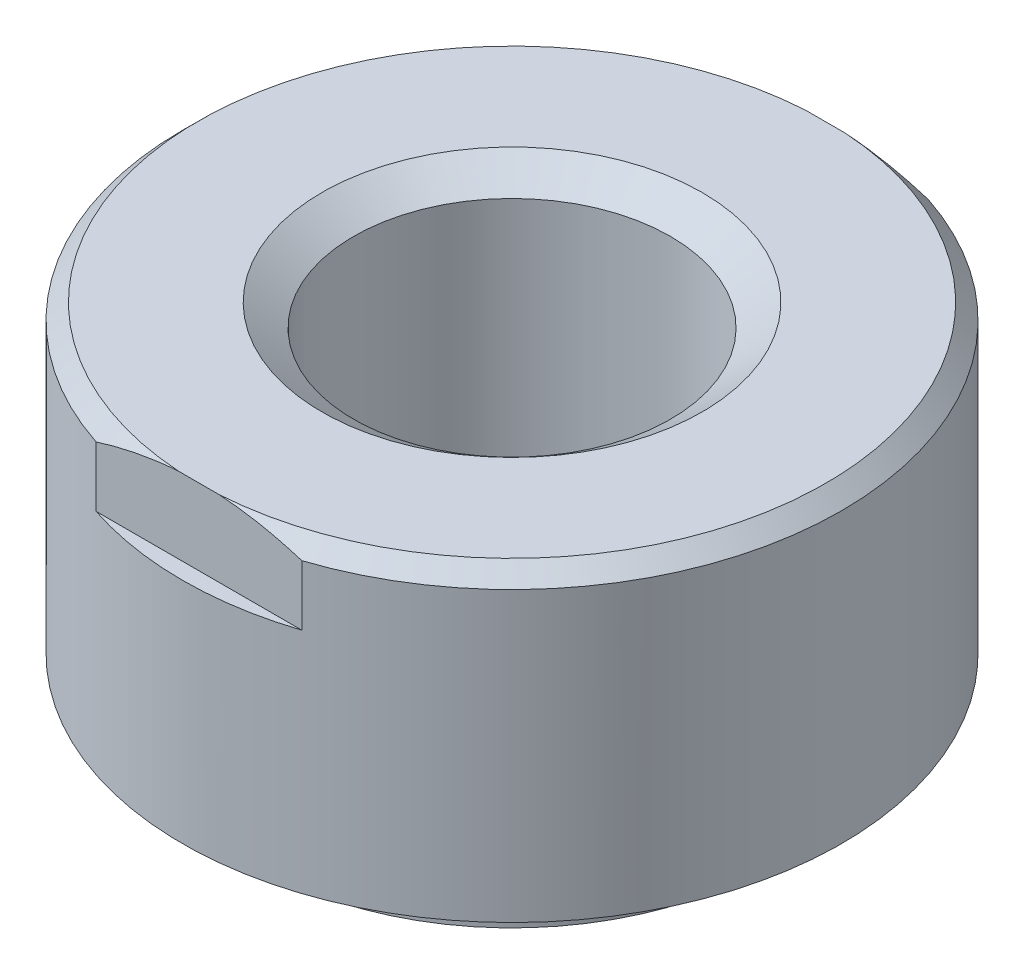
SolidWorks part; units mm, degrees
revolve "Body" add sketch "BodySke"
sketch "BodySke" plane through (0, 0, 0) normal (0, 0, 1) x (1, 0, 0)
  line L0 (5.9003, 0) -> (6.3373, 0)
  line L1 (8.255, 0) -> (8.255, 7.62)
  line L2 (8.255, 7.62) -> (3.9688, 7.62)
  line L3 (3.9688, 7.62) -> (3.9688, -1.4732)
  line L4 (3.9688, -1.4732) -> (6.3373, -1.4732)
  line L5 (6.3373, -1.4732) -> (6.3373, -1.3462)
  line L6 (6.3373, -1.3462) -> (5.9003, -0.5893)
  line L7 (1.016, 1.5875) -> (3.6522, 1.5875) construction
  line L8 (6.3373, -0.5893) -> (7.2961, -0.5893)
  line L9 (0, 0) -> (0, 15.24) construction
  line L10 (5.9003, -0.5893) -> (5.9003, 0)
  line L11 (7.2961, -0.5893) -> (7.2961, 0)
  line L12 (6.3373, -0.5893) -> (6.3373, 0)
  line L13 (7.2961, 0) -> (8.255, 0)
  dimension "D1" = 60
  dimension "E_dia" = 16.51
  dimension "C_dia" = 12.6746
  dimension "A_ht" = 1.4732
  dimension "T_ht" = 7.62
  dimension "Thread_min" = 7.9375
  dimension "C_len" = 0.127
  dimension "Clinching_ht" = 0.5893
  dimension "Advance" = 1.5875
  dimension "Clinching_dia" = 14.5923
cosmetic thread "ThreadCosmetic" [suppressed]
revolve "EndChamfer" cut sketch "EndChamferSke" angle 360 about L0
sketch "EndChamferSke" plane through (0, 0, 0) normal (0, 0, 1) x (1, 0, 0)
  line L0 (0, -2.54) -> (0, 7.62) construction
  line L1 (0, 0) -> (0, 15.24) construction
  line L2 (4.7625, -1.7272) -> (4.7625, -1.4707)
  line L3 (4.7625, -1.4707) -> (3.9688, -0.9151)
  line L4 (3.9688, -0.9151) -> (3.9688, -1.7272)
  line L5 (3.9688, -1.7272) -> (4.7625, -1.7272)
  line L6 (4.7625, 7.62) -> (3.9688, 7.0644)
  line L8 (3.9688, 7.0644) -> (3.9688, 7.62)
  line L9 (4.7625, 7.62) -> (3.9688, 7.62)
  line L10 (3.9688, 7.62) -> (-3.9688, 7.62) construction
  line L11 (-6.3373, -1.4732) -> (6.3373, -1.4732) construction
  dimension "D1" = 0.254
  dimension "Thread_nominal" = 9.525
  dimension "D2" = 34.99
  dimension "Thread_min" = 7.9375
  dimension "Inset" = 0.0025
ref_plane "Plane1" through (0, 0, 0) normal (0, 0, 1) x (1, 0, 0)
ref_plane "Plane2" through (0, 0, 0) normal (0, 1, 0) x (1, 0, 0)
ref_plane "Plane3" through (0, 0, 0) normal (1, 0, 0) x (0, 0, -1)
chamfer "Chamfer" distance 0.3969 1 edges at (0, 7.62, -8.255)
sketch "FlatsSke" plane through (0, 7.62, 0) normal (0, 1, 0) x (-1, 0, 0)
  line L0 (-8.255, 7.8423) -> (8.255, 7.8423)
  line L1 (8.255, 7.8423) -> (8.255, 8.6678)
  line L2 (8.255, 8.6678) -> (-8.255, 8.6678)
  line L3 (-8.255, 8.6678) -> (-8.255, 7.8423)
  line L4 (-8.255, -7.8423) -> (8.255, -7.8422)
  line L5 (8.255, -7.8422) -> (8.255, -8.6678)
  line L6 (8.255, -8.6678) -> (-8.255, -8.6678)
  line L7 (-8.255, -8.6678) -> (-8.255, -7.8423)
  line L8 (0, 9.144) -> (0, -9.144) construction
  line L9 (-9.144, 0) -> (9.144, 0) construction
  dimension "D1" = 16.51
  dimension "D2" = 15.6845
  dimension "D3" = 17.3355
extrude "Flats" cut sketch "FlatsSke" against normal blind 1.905
ref_plane "Plane4" through (0, -0.5486, 0) normal (0, 1, 0) x (-1, 0, 0)
sketch "ThdSchSke" plane through (0, 0, 0) normal (0, 0, 1) x (1, 0, 0)
  line L0 (0, -5.08) -> (0, 7.62) construction
  line L1 (0, 0) -> (0, 15.24) construction
  line L2 (0, -1.4707) -> (4.7625, -1.4707) construction
  line L4 (4.7625, -1.4707) -> (3.9688, -0.9149)
  line L6 (4.7625, -1.4707) -> (3.9688, -2.0264)
  line L7 (3.9688, -0.9149) -> (3.9688, -2.0264)
  line L8 (4.7625, -1.4707) -> (-4.7625, -1.4707) construction
  dimension "Thread_nominal" = 9.525
revolve "ThreadSchematic" [suppressed] cut sketch "ThdSchSke" angle 360 about L0
pattern_linear "ThdSchPat" [suppressed]
sketch "CliCutSke" plane through (0, -0.5893, 0) normal (0, -1, 0) x (1, 0, 0)
  line L0 (0, 0) -> (0, 8.382) construction
  line L1 (0, 0) -> (0.9523, 7.2337) construction
  circle A0 centre (0.9523, 7.2337) radius 0.8255
  circle A1 centre (0, 0) radius 7.2961 construction
extrude "ClinchingCut" cut sketch "CliCutSke" against normal blind 0.5893
pattern_circular "ClinchingCutPat" count 24 every 15 about axis through (0, 0, 0) along (0, 1, 0) of "ClinchingCut"
equation "' \"A_ht@BodySke\" = 0.058"
equation "' \"C_dia@BodySke\" = 0.499"
equation "' \"E_dia@BodySke\" = 0.65"
equation "' \"T_ht@BodySke\" = 0.3"
equation "' \"Advance@BodySke\" = 0.0625"
equation "' \"Thread_min@BodySke\" = 0.3125"
equation "' \"Thread_nominal@ThreadCosmetic\" = 0.375"
equation "\"Count@ClinchingCutPat\" = 24"
equation "\"Angle@ClinchingCutPat\" = 360 / \"Count@ClinchingCutPat\""
equation "\"Half_angle@CliCutSke\" = 180 / \"Count@ClinchingCutPat\""
equation "\"Cut_dia@CliCutSke\" = \"E_dia@BodySke\" * 0.1"
equation "\"Clinching_dia@BodySke\" = ( \"E_dia@BodySke\" + \"C_dia@BodySke\" ) /2"
equation "\"Clinching_ht@BodySke\" = \"A_ht@BodySke\" * 0.4"
equation "\"Clinching_ht@ClinchingCut\" =  \"A_ht@BodySke\" * 0.4"
equation "\"D1@FlatsSke\" = \"E_dia@BodySke\""
equation "\"D2@FlatsSke\" = \"E_dia@BodySke\" * 0.95"
equation "\"D3@FlatsSke\" = \"E_dia@BodySke\" * 1.05"
equation "\"Depth@Flats\" = \"T_ht@BodySke\" * 0.25"
equation "\"Width@Chamfer\" = ( \"Thread_nominal@ThreadCosmetic\" - \"Thread_min@BodySke\" ) / 4"
equation "\"Thread_nominal@EndChamferSke\" = \"Thread_nominal@ThreadCosmetic\""
equation "\"Thread_min@EndChamferSke\" = \"Thread_min@BodySke\""
equation "\"D2@EndChamferSke\" = \"Vee_angle@ThdSchSke\" / 2 - 0.01"
equation "\"Thread_nominal@ThdSchSke\" = \"Thread_nominal@ThreadCosmetic\""
equation "\"Thread_min@ThdSchSke\" = \"Thread_min@BodySke\""
equation "\"Num_threads@ThdSchPat\" = int(  ( \"A_ht@BodySke\" + \"T_ht@BodySke\" - \"Inset@EndChamferSke\" ) / \"Advance@BodySke\" + 0.999 )  + 1"
equation "\"Advance@ThdSchPat\" = (  \"A_ht@BodySke\" + \"T_ht@BodySke\" - \"Inset@EndChamferSke\"  ) /  (\"Num_threads@ThdSchPat\" - 1) 'relax it"
